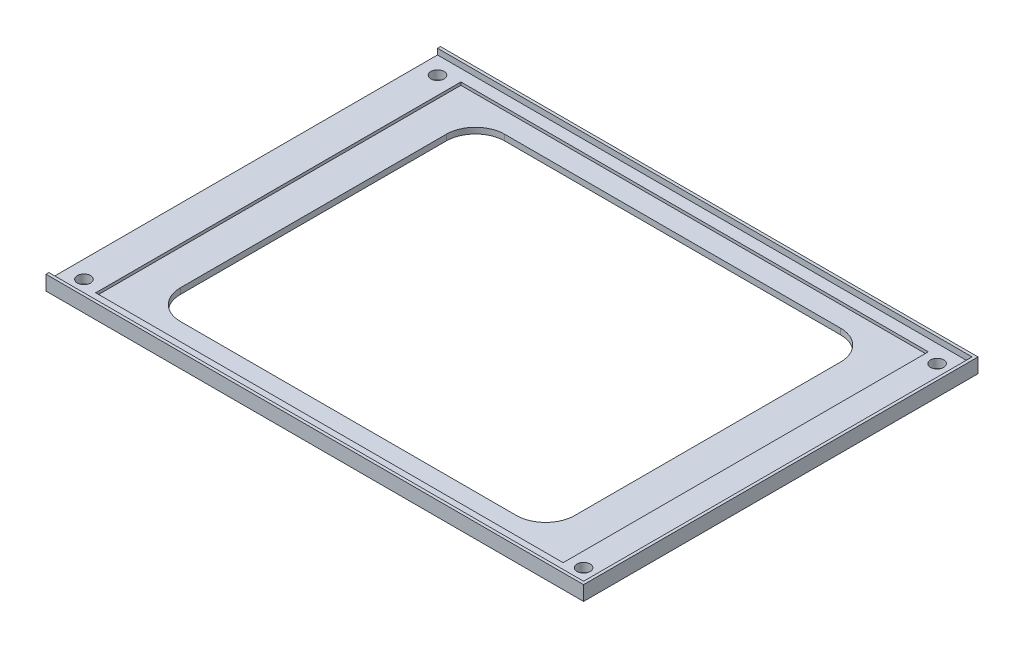
SolidWorks part; units mm, degrees
ref_plane "Front Plane" through (0, 0, 0) normal (0, 0, 1) x (1, 0, 0)
ref_plane "Top Plane" through (0, 0, 0) normal (0, 1, 0) x (1, 0, 0)
ref_plane "Right Plane" through (0, 0, 0) normal (1, 0, 0) x (0, 0, -1)
sketch "Sketch2" plane through (0, 0, 0) normal (0, 1, 0) x (1, 0, 0)
  line L0 (129.7228, 44.5) -> (129.7228, -44.5) construction
  line L1 (4.7228, 55.5) -> (119.7228, 55.5)
  line L2 (-5.2772, 45.5) -> (-5.2772, -45.5)
  line L3 (4.7228, -55.5) -> (119.7228, -55.5)
  line L4 (129.7228, 45.5) -> (129.7228, -45.5)
  line L5 (-29.2772, 67.5) -> (154.7228, 67.5)
  line L6 (-29.2772, 67.5) -> (-29.2772, -67.5)
  line L7 (-29.2772, -67.5) -> (154.7228, -67.5)
  line L8 (154.7228, 67.5) -> (154.7228, -67.5)
  line L9 (-29.2772, -66.5) -> (-29.2772, -3.0875) construction
  line L10 (-5.2772, -54.5) -> (-5.2772, 54.5) construction
  arc A0 (4.7228, 55.5) -> (-5.2772, 45.5) centre (4.7228, 45.5) ccw
  arc A1 (-5.2772, -45.5) -> (4.7228, -55.5) centre (4.7228, -45.5) ccw
  arc A2 (119.7228, -55.5) -> (129.7228, -45.5) centre (119.7228, -45.5) ccw
  arc A3 (119.7228, 55.5) -> (129.7228, 45.5) centre (119.7228, 45.5) cw
  point P10 (154.7228, 0)
  dimension "D1" = 10
  dimension "D2" = 12
  dimension "D3" = 12
  dimension "D5" = 135
  dimension "D6" = 184
extrude "Boss-Extrude1" add sketch "Sketch2" along normal blind 2
sketch "Sketch3" plane through (0, 2, 0) normal (0, 1, 0) x (1, 0, 0)
  line L1 (-29.2772, 67.5) -> (154.7228, 67.5)
  line L2 (-29.2772, 67.5) -> (-29.2772, -67.5)
  line L3 (-29.2772, -67.5) -> (154.7228, -67.5)
  line L4 (154.7228, 67.5) -> (154.7228, -67.5)
  line L5 (-17.2772, 62.5) -> (142.7228, 62.5)
  line L6 (-17.2772, 62.5) -> (-17.2772, -62.5)
  line L7 (-17.2772, -62.5) -> (142.7228, -62.5)
  line L8 (142.7228, 62.5) -> (142.7228, -62.5)
  point P10 (142.7228, 0)
  point P11 (154.7228, 0)
  point P12 (62.7228, 62.5)
  point P13 (62.7228, 67.5)
  dimension "D1" = 160
  dimension "D2" = 125
extrude "Boss-Extrude2" add sketch "Sketch3" along normal blind 1
sketch "Sketch4" plane through (0, 3, 0) normal (0, 1, 0) x (1, 0, 0)
  line L1 (-29.2772, 67.5) -> (154.7228, 67.5)
  line L2 (-29.2772, 67.5) -> (-29.2772, -67.5)
  line L3 (-29.2772, -67.5) -> (154.7228, -67.5)
  line L4 (154.7228, 67.5) -> (154.7228, -67.5)
  line L5 (-29.2772, 66.5) -> (153.7228, 66.5)
  line L7 (-29.2772, -66.5) -> (153.7228, -66.5)
  line L8 (153.7228, 66.5) -> (153.7228, -66.5)
  line M9 (-29.2772, 67.5) -> (-29.2772, -67.5)
  line M10 (-29.2772, -67.5) -> (154.7228, -67.5)
  line M11 (154.7228, -67.5) -> (154.7228, 67.5)
  line M12 (154.7228, 67.5) -> (-29.2772, 67.5)
  dimension "D2" = 1
  dimension "D3" = 1
  dimension "D4" = 1
extrude "Boss-Extrude3" add sketch "Sketch4" along normal blind 2 contours L5 L8 L7 M9 M10 M11 M12
sketch "Sketch5" plane through (0, 0, 0) normal (0, -1, 0) x (1, 0, 0)
  line L0 (154.7228, -67.5) -> (-29.2772, -67.5) construction
  line L1 (154.7228, 67.5) -> (154.7228, -67.5) construction
  line L2 (-29.2772, -67.5) -> (-29.2772, 67.5) construction
  line L3 (-29.2772, 67.5) -> (154.7228, 67.5) construction
  circle A0 centre (-23.2772, 60.5) radius 2.25
  circle A1 centre (-23.2772, -60.5) radius 2.25
  circle A2 centre (147.7228, -60.5) radius 2.25
  circle A3 centre (147.7228, 60.5) radius 2.25
  dimension "D5" = 4.5
  dimension "D1" = 7
  dimension "D2" = 7
  dimension "D3" = 6
  dimension "D4" = 7
extrude "Cut-Extrude1" cut sketch "Sketch5" against normal up to next
